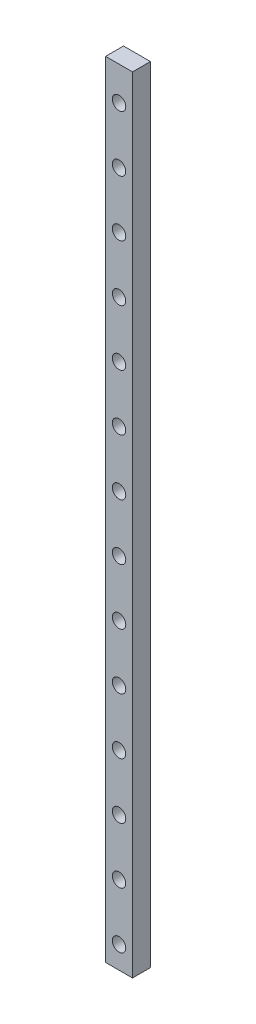
SolidWorks part; units mm, degrees
ref_plane "前视基准面" through (0, 0, 0) normal (0, 0, 1) x (1, 0, 0)
ref_plane "上视基准面" through (0, 0, 0) normal (0, 1, 0) x (1, 0, 0)
ref_plane "右视基准面" through (0, 0, 0) normal (1, 0, 0) x (0, 0, -1)
sketch "草图1" plane through (0, 0, 0) normal (0, 1, 0) x (1, 0, 0)
  line L1 (6, -4) -> (-6, -4)
  line L2 (6, -4) -> (6, 4)
  line L3 (6, 4) -> (-6, 4)
  line L4 (-6, -4) -> (-6, 4)
  line L5 (6, -4) -> (-6, 4) construction
  line L6 (6, 4) -> (-6, -4) construction
  point P0 (0, 0)
  dimension "D1" = 12
  dimension "D2" = 8
extrude "凸台-拉伸1" add sketch "草图1" along normal blind 350
sketch "草图2" plane through (0, 0, 4) normal (0, 0, 1) x (1, 0, 0)
  line L0 (0, -1000) -> (0, 49000) construction
  line L1 (-6, 0) -> (6, 0) construction
  circle A0 centre (0, 10) radius 3
  dimension "D1" = 6
  dimension "D2" = 10
extrude "切除-拉伸1" cut sketch "草图2" against normal blind 4.5
sketch "草图3" plane through (0, 0, -0.5) normal (0, 0, 1) x (1, 0, 0)
  circle A0 centre (0, 10) radius 1.75
  circle A1 centre (0, 10) radius 3
  circle A2 centre (0, 10) radius 3 construction
  dimension "D2" = 3.5
  dimension "D1" = 0
extrude "切除-拉伸2" cut sketch "草图3" against normal blind 4.5
pattern_linear "阵列(线性)1" count 14 spacing 25 along (0, 1, 0) of "切除-拉伸2", "切除-拉伸1"
